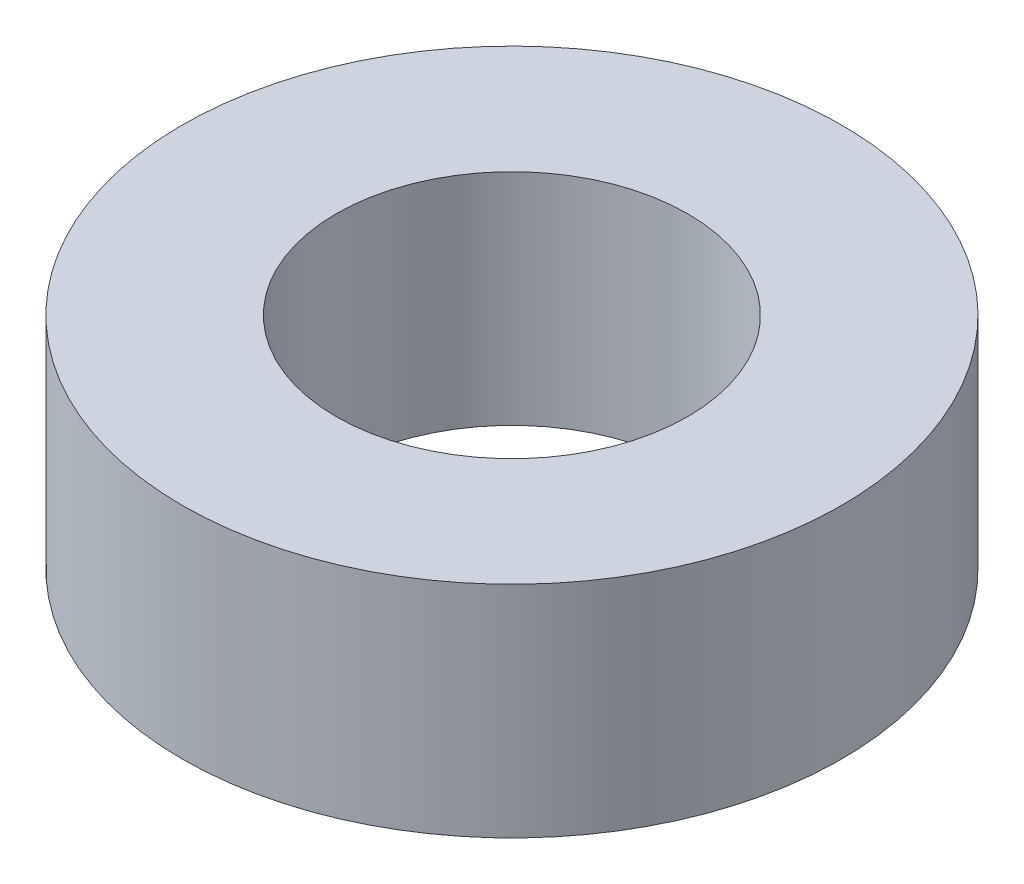
SolidWorks part; units mm, degrees
ref_plane "Front" through (0, 0, 0) normal (0, 0, 1) x (1, 0, 0)
ref_plane "Top" through (0, 0, 0) normal (0, 1, 0) x (1, 0, 0)
ref_plane "Right" through (0, 0, 0) normal (1, 0, 0) x (0, 0, -1)
sketch "Sketch1" plane through (0, 0, 0) normal (0, 1, 0) x (1, 0, 0)
  circle A0 centre (0, 0) radius 1.6
  circle A1 centre (0, 0) radius 3
  dimension "D1" = 3.2
  dimension "D2" = 6
extrude "Boss-Extrude1" add sketch "Sketch1" along normal blind 2
